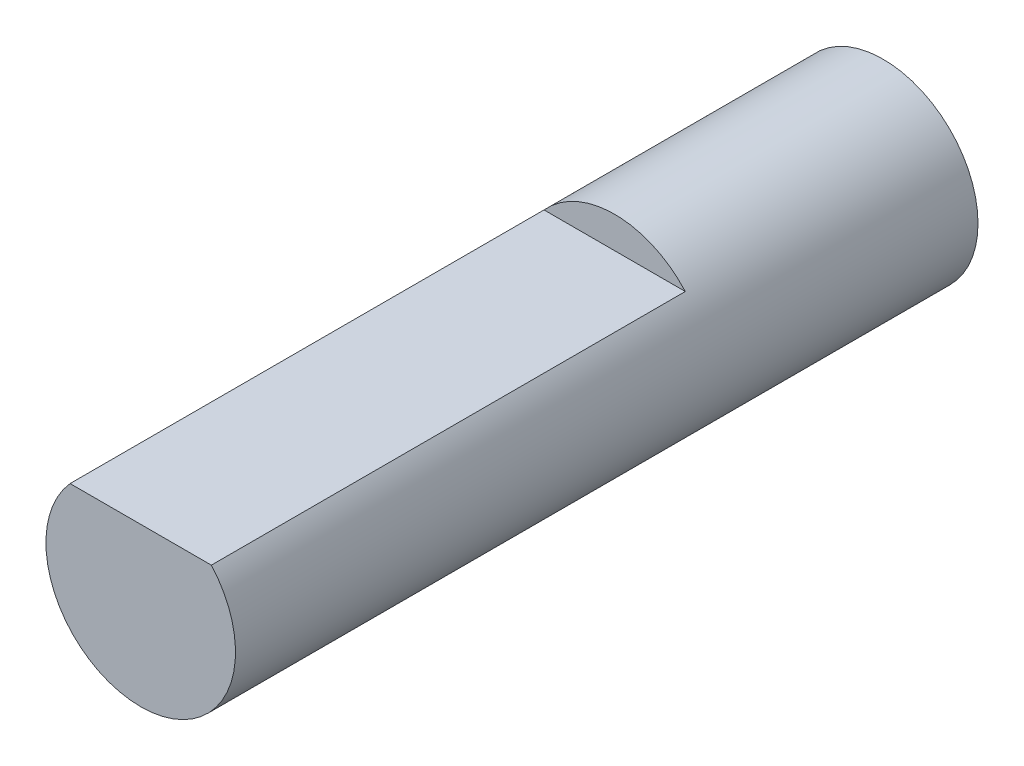
SolidWorks part; units mm, degrees
ref_plane "Front Plane" through (0, 0, 0) normal (0, 0, 1) x (1, 0, 0)
ref_plane "Top Plane" through (0, 0, 0) normal (0, 1, 0) x (1, 0, 0)
ref_plane "Right Plane" through (0, 0, 0) normal (1, 0, 0) x (0, 0, -1)
sketch "Sketch1" plane through (0, 0, 0) normal (0, 0, 1) x (1, 0, 0)
  circle A0 centre (0, 0) radius 3.81
  dimension "D1" = 7.62
extrude "Boss-Extrude1" add sketch "Sketch1" along normal blind 29.845
sketch "Sketch2" plane through (0, 0, 29.845) normal (0, 0, 1) x (1, 0, 0)
  line L0 (-2.8398, 2.54) -> (2.8398, 2.54)
  circle A1 centre (0, 0) radius 3.81
  circle A2 centre (0, 0) radius 3.81
  circle M3 centre (0, 0) radius 3.81
  dimension "D2" = 6.35
  dimension "D1" = 0
extrude "Cut-Extrude1" cut sketch "Sketch2" against normal blind 19.05 contours L0 M3
